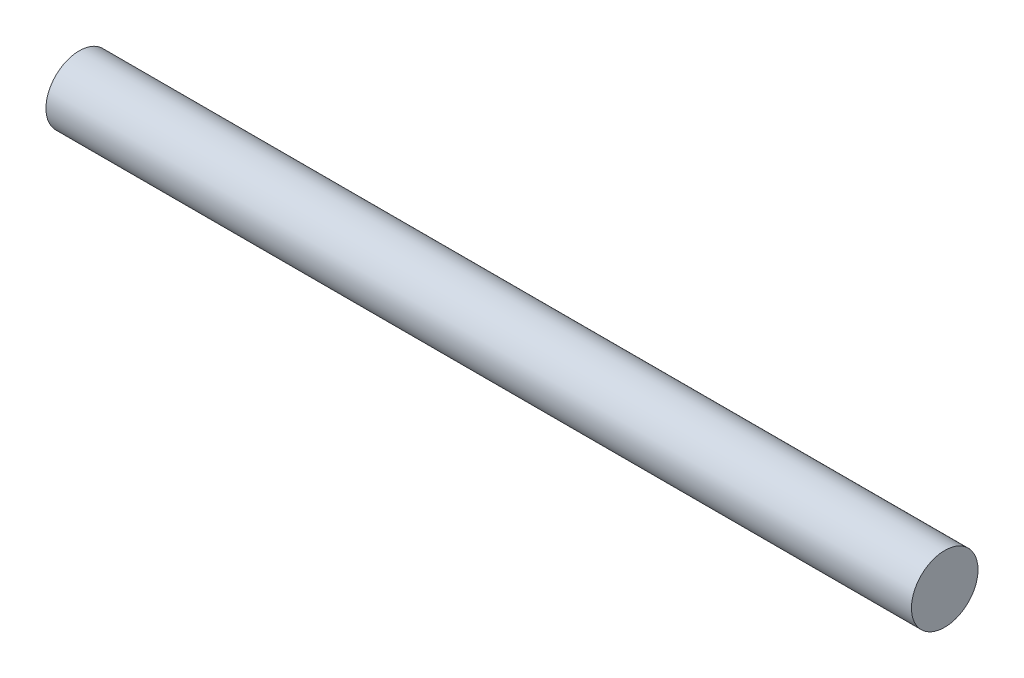
SolidWorks part; units mm, degrees
material "Chrome Stainless Steel"
ref_plane "Front Plane" through (0, 0, 0) normal (0, 0, 1) x (1, 0, 0)
ref_plane "Top Plane" through (0, 0, 0) normal (0, 1, 0) x (1, 0, 0)
ref_plane "Right Plane" through (0, 0, 0) normal (1, 0, 0) x (0, 0, -1)
sketch "BaseS" plane through (0, 0, 0) normal (1, 0, 0) x (0, 0, -1)
  circle A0 centre (0, 0) radius 1.5
  dimension "Diameter" = 3
extrude "Base" add sketch "BaseS" along normal mid plane 39
